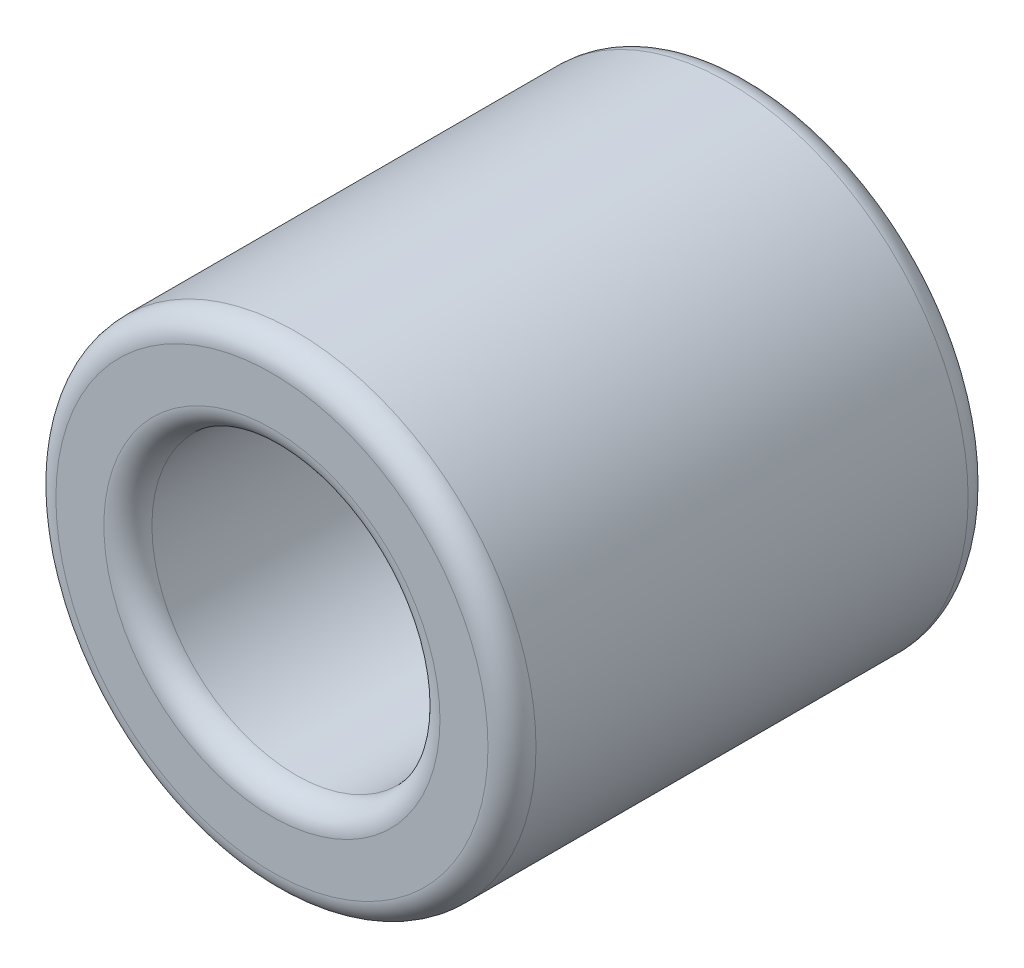
SolidWorks part; units mm, degrees
ref_plane "前视基准面" through (0, 0, 0) normal (0, 0, 1) x (1, 0, 0)
ref_plane "上视基准面" through (0, 0, 0) normal (0, 1, 0) x (1, 0, 0)
ref_plane "右视基准面" through (0, 0, 0) normal (1, 0, 0) x (0, 0, -1)
other "Configuration Table"
sketch "草图1" plane through (0, 0, 0) normal (0, 0, 1) x (1, 0, 0)
  circle A0 centre (0, 0) radius 3
  circle A1 centre (0, 0) radius 5
extrude "凸台-拉伸1" add sketch "草图1" along normal blind 10
fillet "圆角1" radius 0.5 4 edges at (5, 0, 0) (3, 0, 0) (3, 0, 10) (5, 0, 10)
